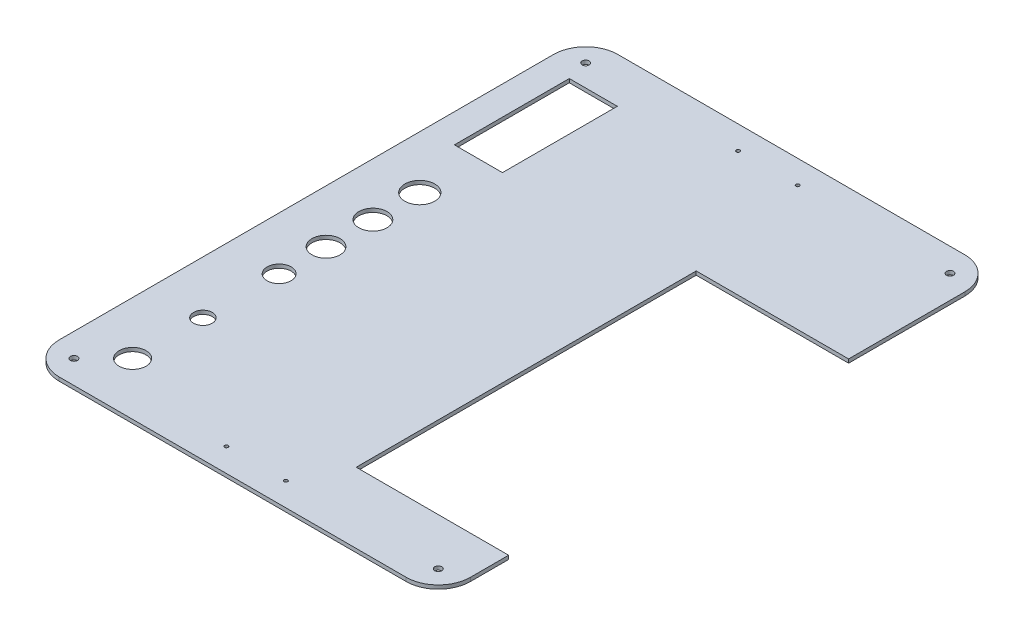
SolidWorks part; units mm, degrees
ref_plane "Front Plane" through (0, 0, 0) normal (0, 0, 1) x (1, 0, 0)
ref_plane "Top Plane" through (0, 0, 0) normal (0, 1, 0) x (1, 0, 0)
ref_plane "Right Plane" through (0, 0, 0) normal (1, 0, 0) x (0, 0, -1)
sketch "Sketch1" plane through (0, 0, 0) normal (0, 1, 0) x (1, 0, 0)
  line L1 (-147.955, 238.252) -> (147.955, 238.252)
  line L2 (-175.387, 210.82) -> (-175.387, -210.82)
  line L3 (-147.955, -238.252) -> (147.955, -238.252)
  line L4 (175.387, 210.82) -> (175.387, -210.82)
  line L5 (-175.387, 238.252) -> (175.387, -238.252) construction
  line L6 (-175.387, -238.252) -> (175.387, 238.252) construction
  arc A0 (147.955, -238.252) -> (175.387, -210.82) centre (147.955, -210.82) ccw
  arc A1 (-175.387, -210.82) -> (-147.955, -238.252) centre (-147.955, -210.82) ccw
  arc A2 (-147.955, 238.252) -> (-175.387, 210.82) centre (-147.955, 210.82) ccw
  arc A3 (147.955, 238.252) -> (175.387, 210.82) centre (147.955, 210.82) cw
  point P0 (0, 0)
  dimension "D3" = 27.432
  dimension "D1" = 350.774
  dimension "D2" = 476.504
extrude "Boss-Extrude1" add sketch "Sketch1" along normal blind 3.175
sketch "Sketch2" plane through (0, 3.175, 0) normal (0, 1, 0) x (1, 0, 0)
  line L1 (175.387, 111.748) -> (45.387, 111.748)
  line L4 (45.387, 111.748) -> (45.387, -178.252)
  line L5 (-147.955, -238.252) -> (147.955, -238.252) construction
  line L6 (175.387, -210.82) -> (175.387, 210.82) construction
  line L7 (45.387, -178.252) -> (175.387, -178.252)
  line L8 (175.387, -178.252) -> (175.387, 111.748)
  dimension "D1" = 130
  dimension "D2" = 350
  dimension "D3" = 60
extrude "Cut-Extrude1" cut sketch "Sketch2" against normal blind 10
sketch "Sketch3" plane through (0, 3.175, 0) normal (0, 1, 0) x (1, 0, 0)
  line L0 (-130.387, 238.252) -> (-130.387, -238.252) construction
  line L1 (-147.387, -119.752) -> (-113.387, -119.752) construction
  line L2 (-147.387, -119.752) -> (-147.387, -146.752) construction
  line L3 (-147.387, -146.752) -> (-113.387, -146.752) construction
  line L4 (-113.387, -119.752) -> (-113.387, -146.752) construction
  line L5 (-147.387, -119.752) -> (-113.387, -146.752) construction
  line L6 (-147.387, -146.752) -> (-113.387, -119.752) construction
  line L7 (147.955, 238.252) -> (-147.955, 238.252) construction
  line L8 (-147.955, -238.252) -> (147.955, -238.252) construction
  line L9 (-130.387, 0) -> (0, 0) construction
  line L10 (-175.387, 210.82) -> (-175.387, -210.82) construction
  line L11 (-155.387, 218.252) -> (155.387, 218.252) construction
  line L12 (-150.887, 199.748) -> (-109.887, 199.748)
  line L13 (-150.887, 199.748) -> (-150.887, 101.748)
  line L14 (-150.887, 101.748) -> (-109.887, 101.748)
  line L15 (-109.887, 199.748) -> (-109.887, 101.748)
  line L16 (-150.887, 199.748) -> (-109.887, 101.748) construction
  line L17 (-150.887, 101.748) -> (-109.887, 199.748) construction
  line L18 (155.387, 218.252) -> (155.387, -218.252) construction
  line L19 (155.387, -218.252) -> (-155.387, -218.252) construction
  line L20 (-155.387, -218.252) -> (-155.387, 218.252) construction
  line L21 (175.387, 111.748) -> (175.387, 210.82) construction
  line L22 (-157.887, 199.248) -> (-102.887, 199.248) construction
  line L23 (-102.887, 199.248) -> (-102.887, 102.248) construction
  line L24 (-102.887, 102.248) -> (-157.887, 102.248) construction
  line L25 (-157.887, 102.248) -> (-157.887, 199.248) construction
  line L26 (-159.687, 197.448) -> (-101.087, 197.448) construction
  line L27 (-25.4, 218.252) -> (25.4, 218.252) construction
  line L28 (-25.4, -218.252) -> (25.4, -218.252) construction
  circle A0 centre (-130.387, -193.252) radius 11.5
  circle A1 centre (-130.387, -133.252) radius 8
  circle A2 centre (-130.387, -68.252) radius 10.25
  circle A3 centre (-130.387, -28.252) radius 12
  circle A4 centre (-130.387, 11.748) radius 12
  circle A5 centre (-130.387, 51.748) radius 12.75
  circle A6 centre (-130.387, 193.252) radius 9.5 construction
  circle A7 centre (155.387, 218.252) radius 3
  circle A8 centre (155.387, -218.252) radius 3
  circle A9 centre (-155.387, -218.252) radius 3
  circle A10 centre (-155.387, 218.252) radius 3
  circle A11 centre (-102.887, 197.448) radius 1.8 construction
  circle A12 centre (-102.887, 104.048) radius 1.8 construction
  circle A13 centre (-157.887, 104.048) radius 1.8 construction
  circle A14 centre (-157.887, 197.448) radius 1.8 construction
  circle A15 centre (-25.4, 218.252) radius 1.5
  circle A16 centre (25.4, 218.252) radius 1.5
  circle A17 centre (-25.4, -218.252) radius 1.5
  circle A18 centre (25.4, -218.252) radius 1.5
  point P19 (-130.387, 0)
  point P23 (-130.387, 150.748)
  point P57 (-102.887, 150.748)
  point P61 (-130.387, 197.448)
  point P69 (0, 218.252)
  point P70 (0, -218.252)
  dimension "D1" = 23
  dimension "D2" = 16
  dimension "D5" = 20.5
  dimension "D6" = 24
  dimension "D7" = 24
  dimension "D8" = 25.5
  dimension "D11" = 60
  dimension "D12" = 170
  dimension "D13" = 40
  dimension "D14" = 40
  dimension "D15" = 40
  dimension "D16" = 19
  dimension "D17" = 45
  dimension "D20" = 50
  dimension "D21" = 6
  dimension "D22" = 20
  dimension "D27" = 3.6
  dimension "D29" = 3
  dimension "D3" = 27
  dimension "D4" = 34
  dimension "D9" = 45
  dimension "D10" = 45
  dimension "D18" = 98
  dimension "D19" = 41
  dimension "D23" = 20
  dimension "D24" = 20
  dimension "D25" = 20
  dimension "D26" = 97
  dimension "D28" = 58.6
  dimension "D30" = 50.8
  dimension "D31" = 20
  dimension "D32" = 20
extrude "Cut-Extrude2" cut sketch "Sketch3" against normal through all
